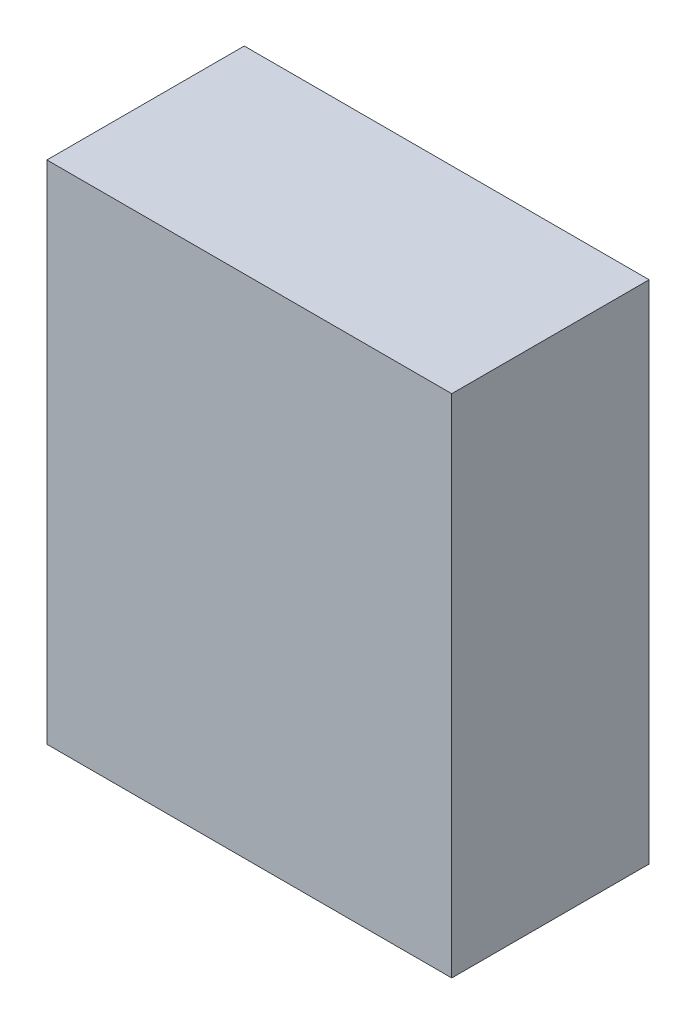
SolidWorks part; units mm, degrees
ref_plane "Front Plane" through (0, 0, 0) normal (0, 0, 1) x (1, 0, 0)
ref_plane "Top Plane" through (0, 0, 0) normal (0, 1, 0) x (1, 0, 0)
ref_plane "Right Plane" through (0, 0, 0) normal (1, 0, 0) x (0, 0, -1)
sketch "Sketch1" plane through (0, 0, 0) normal (0, 0, 1) x (1, 0, 0)
  line L1 (-38.4444, 23) -> (1.5556, 23)
  line L2 (-38.4444, 23) -> (-38.4444, -27)
  line L3 (-38.4444, -27) -> (1.5556, -27)
  line L4 (1.5556, 23) -> (1.5556, -27)
  dimension "D1" = 50
  dimension "D2" = 40
extrude "Boss-Extrude1" add sketch "Sketch1" along normal blind 19.5
